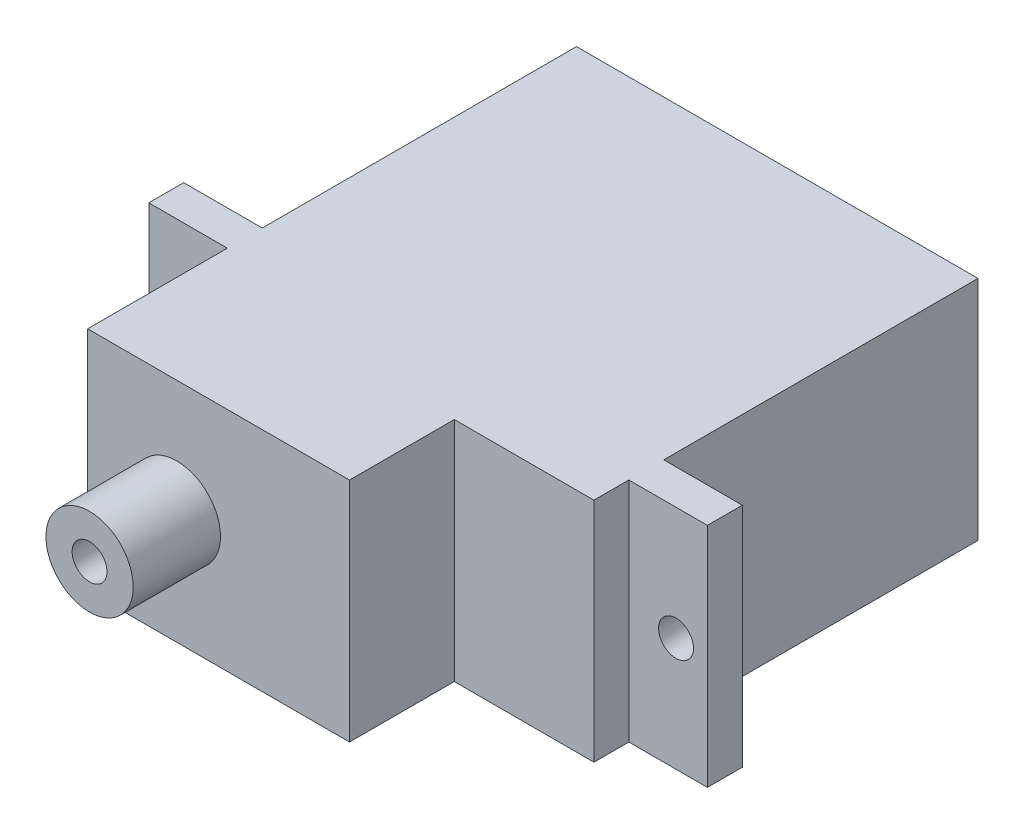
SolidWorks part; units mm, degrees
ref_plane "Front Plane" through (0, 0, 0) normal (0, 0, 1) x (1, 0, 0)
ref_plane "Top Plane" through (0, 0, 0) normal (0, 1, 0) x (1, 0, 0)
ref_plane "Right Plane" through (0, 0, 0) normal (1, 0, 0) x (0, 0, -1)
sketch "Sketch1" plane through (0, 0, 0) normal (0, 0, 1) x (1, 0, 0)
  line L1 (-11.5, 6.5) -> (11.5, 6.5)
  line L2 (-11.5, 6.5) -> (-11.5, -6.5)
  line L3 (-11.5, -6.5) -> (11.5, -6.5)
  line L4 (11.5, 6.5) -> (11.5, -6.5)
  line L5 (-11.5, 6.5) -> (11.5, -6.5) construction
  line L6 (-11.5, -6.5) -> (11.5, 6.5) construction
  point P0 (0, 0)
  dimension "D1" = 23
  dimension "D2" = 13
extrude "Boss-Extrude1" add sketch "Sketch1" along normal blind 18
sketch "Sketch2" plane through (0, 0, 18) normal (0, 0, 1) x (1, 0, 0)
  line L1 (-16, 6.5) -> (16, 6.5)
  line L2 (-16, 6.5) -> (-16, -6.5)
  line L3 (-16, -6.5) -> (16, -6.5)
  line L4 (16, 6.5) -> (16, -6.5)
  line L5 (-16, 6.5) -> (16, -6.5) construction
  line L6 (-16, -6.5) -> (16, 6.5) construction
  point P0 (0, 0)
  dimension "D1" = 32
extrude "Boss-Extrude2" add sketch "Sketch2" along normal blind 2
sketch "Sketch3" plane through (0, 0, 20) normal (0, 0, 1) x (1, 0, 0)
  line L0 (-16, -6.5) -> (16, -6.5) construction
  line L1 (-11.5, 6.5) -> (11.5, 6.5)
  line L2 (-11.5, 6.5) -> (-11.5, -6.5)
  line L3 (-11.5, -6.5) -> (11.5, -6.5)
  line L4 (11.5, 6.5) -> (11.5, -6.5)
  line L5 (-11.5, 6.5) -> (11.5, -6.5) construction
  line L6 (-11.5, -6.5) -> (11.5, 6.5) construction
  point P0 (0, 0)
  dimension "D1" = 23
extrude "Boss-Extrude3" add sketch "Sketch3" along normal blind 2
sketch "Sketch4" plane through (0, 0, 22) normal (0, 0, 1) x (1, 0, 0)
  line L0 (11.5, 6.5) -> (-11.5, 6.5) construction
  line L1 (-11.5, -6.5) -> (3.5, -6.5)
  line L2 (-11.5, -6.5) -> (-11.5, 6.5)
  line L3 (-11.5, 6.5) -> (3.5, 6.5)
  line L4 (3.5, -6.5) -> (3.5, 6.5)
  dimension "D1" = 15
extrude "Boss-Extrude4" add sketch "Sketch4" along normal blind 6
sketch "Sketch5" plane through (0, 0, 28) normal (0, 0, 1) x (1, 0, 0)
  circle A0 centre (-6.3915, 0) radius 2.5
  dimension "D1" = 5
extrude "Boss-Extrude5" add sketch "Sketch5" along normal blind 5
sketch "Sketch6" plane through (0, 0, 33) normal (0, 0, 1) x (1, 0, 0)
  circle A0 centre (-6.3915, 0) radius 1
  dimension "D1" = 2
extrude "Cut-Extrude1" cut sketch "Sketch6" against normal blind 5
sketch "Sketch7" plane through (0, 0, 20) normal (0, 0, 1) x (1, 0, 0)
  circle A0 centre (-13.6891, 0) radius 1
  circle A1 centre (14.2019, 0) radius 1
  dimension "D1" = 2
  dimension "D2" = 2
extrude "Cut-Extrude2" cut sketch "Sketch7" against normal blind 5
